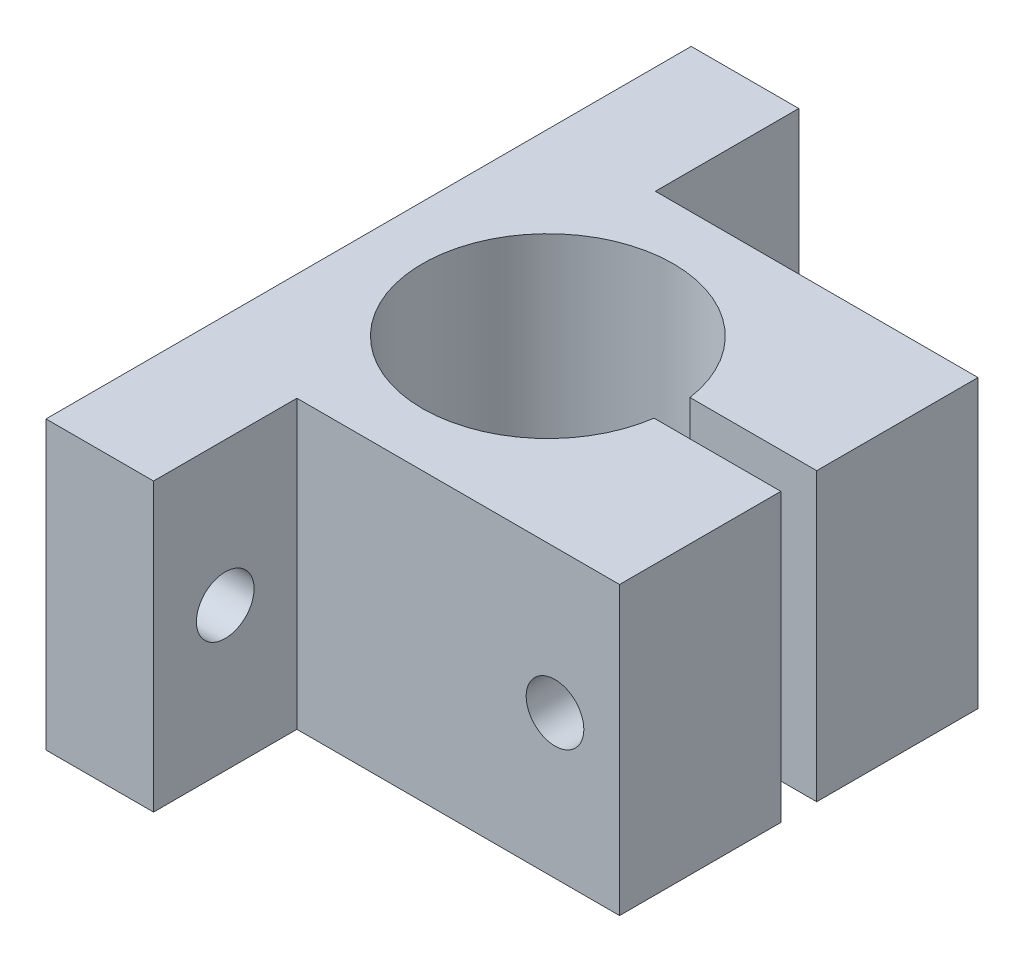
SolidWorks part; units mm, degrees
material "6061 Alloy"
ref_plane "Front Plane" through (0, 0, 0) normal (0, 0, 1) x (1, 0, 0)
ref_plane "Top Plane" through (0, 0, 0) normal (0, 1, 0) x (1, 0, 0)
ref_plane "Right Plane" through (0, 0, 0) normal (1, 0, 0) x (0, 0, -1)
sketch "Sketch1" plane through (0, 0, 0) normal (0, 1, 0) x (1, 0, 0)
  line L1 (-25.4, 28.575) -> (25.4, 28.575)
  line L2 (-25.4, 28.575) -> (-25.4, -28.575)
  line L3 (-25.4, -28.575) -> (25.4, -28.575)
  line L4 (25.4, 28.575) -> (25.4, -28.575)
  line L5 (-25.4, 28.575) -> (25.4, -28.575) construction
  line L6 (-25.4, -28.575) -> (25.4, 28.575) construction
  point P0 (0, 0)
  dimension "D1" = 50.8
  dimension "D2" = 57.15
extrude "Boss-Extrude1" add sketch "Sketch1" along normal mid plane 25.4
sketch "Sketch2" plane through (0, 12.7, 0) normal (0, 1, 0) x (1, 0, 0)
  line L0 (-25.4, 28.575) -> (-25.4, -28.575) construction
  circle A0 centre (-9.525, 0) radius 11.1125
  dimension "D1" = 22.225
  dimension "D2" = 15.875
extrude "Cut-Extrude1" cut sketch "Sketch2" against normal through all
sketch "Sketch11" plane through (0, 12.7, 0) normal (0, 1, 0) x (1, 0, 0)
  line L0 (25.4, 28.575) -> (-25.4, 28.575) construction
  line L1 (12.7, 28.575) -> (25.4, 28.575)
  line L2 (12.7, 28.575) -> (12.7, -28.575)
  line L3 (12.7, -28.575) -> (25.4, -28.575)
  line L4 (25.4, 28.575) -> (25.4, -28.575)
  dimension "D1" = 12.7
extrude "Cut-Extrude4" cut sketch "Sketch11" against normal through all
sketch "Sketch3" plane through (0, 12.7, 0) normal (0, 1, 0) x (1, 0, 0)
  line L0 (-25.4, -28.575) -> (12.7, -28.575) construction
  line L1 (12.7, 28.575) -> (-15.875, 28.575)
  line L2 (12.7, 28.575) -> (12.7, 15.875)
  line L3 (12.7, 15.875) -> (-15.875, 15.875)
  line L4 (-15.875, 28.575) -> (-15.875, 15.875)
  line L5 (-15.875, -28.575) -> (12.7, -28.575)
  line L6 (-15.875, -28.575) -> (-15.875, -15.875)
  line L7 (-15.875, -15.875) -> (12.7, -15.875)
  line L8 (12.7, -28.575) -> (12.7, -15.875)
  line L10 (-25.4, 28.575) -> (-25.4, -28.575) construction
  line L11 (12.7, 28.575) -> (12.7, -28.575) construction
  line L12 (12.7, 28.575) -> (-25.4, 28.575) construction
  dimension "D1" = 9.525
  dimension "D2" = 12.7
extrude "Cut-Extrude2" cut sketch "Sketch3" against normal through all
hole_wizard "#10 Clearance Hole1" positions "Sketch5" profile "Sketch4" hole size "#10" standard "ANSI Inch" end condition up to next
sketch "Sketch5" plane through (-15.875, 0, 0) normal (1, 0, 0) x (0, 0, -1)
  line L22 (-22.225, 12.7) -> (-22.225, -12.7) construction
  line L26 (22.225, 12.7) -> (22.225, -12.7) construction
  line L29 (28.575, -12.7) -> (28.575, 12.7) construction
  line L30 (28.575, -12.7) -> (15.875, -12.7) construction
  line L31 (28.575, 12.7) -> (15.875, 12.7) construction
  line L32 (-28.575, -12.7) -> (-28.575, 12.7) construction
  line L33 (-15.875, -12.7) -> (-28.575, -12.7) construction
  line L34 (-15.875, 12.7) -> (-28.575, 12.7) construction
  point P558 (22.225, 0)
  point P598 (-22.225, 0)
  dimension "D1" = 6.35
  dimension "D2" = 6.35
sketch "Sketch4" plane through (-15.875, 0, -22.225) normal (0, 1, 0) x (0, 0, -1)
  line L0 (0, 0) -> (0, 9.525)
  line L1 (0, 9.525) -> (2.5527, 9.525)
  line L2 (2.5527, 9.525) -> (2.5527, 0)
  line L5 (2.5527, 0) -> (0, 0)
  line L11 (0, -6.35) -> (0, 107.95) construction
  dimension "Thru Hole Dia." = 5.1054
  dimension "Thru Hole Depth" = 9.525
sketch "Sketch6" plane through (12.7, 0, 0) normal (1, 0, 0) x (0, 0, -1)
  line L1 (0, 18.545) -> (0, -18.545) construction
  line L2 (-1.5875, 18.545) -> (1.5875, 18.545)
  line L3 (-1.5875, 18.545) -> (-1.5875, -18.545)
  line L4 (-1.5875, -18.545) -> (1.5875, -18.545)
  line L6 (1.5875, 18.545) -> (1.5875, -18.545)
  dimension "D1" = 3.175
extrude "Cut-Extrude3" cut sketch "Sketch6" against normal blind 24.13
hole_wizard "#10 Clearance Hole2" positions "Sketch8" profile "Sketch9" hole size "#10" standard "ANSI Inch" end condition through all
sketch "Sketch8" plane through (0, 0, 15.875) normal (0, 0, 1) x (1, 0, 0)
  line L0 (6.985, 12.7) -> (6.985, -12.7) construction
  line L1 (12.7, 12.7) -> (-15.875, 12.7) construction
  line L2 (12.7, -12.7) -> (-15.875, -12.7) construction
  line L4 (12.7, -12.7) -> (12.7, 12.7) construction
  point P9 (6.985, 0)
  dimension "D3" = 5.715
sketch "Sketch9" plane through (6.985, 0, 15.875) normal (1, 0, 0) x (0, -1, 0)
  line L0 (0, 0) -> (0, 44.45)
  line L1 (0, 44.45) -> (2.5527, 44.45)
  line L2 (2.5527, 44.45) -> (2.5527, 0)
  line L5 (2.5527, 0) -> (0, 0)
  line L11 (0, -6.35) -> (0, 107.95) construction
  dimension "Thru Hole Dia." = 5.1054
  dimension "Thru Hole Depth" = 44.45
sketch "Sketch10" plane through (-15.875, 0, 0) normal (1, 0, 0) x (0, 0, -1)
  circle A0 centre (22.225, 0) radius 4.7625 construction
  dimension "D1" = 9.525
fillet "Fillet1" [suppressed] radius 3.175
chamfer "Chamfer2" [suppressed] distance 0.508 angle 45
